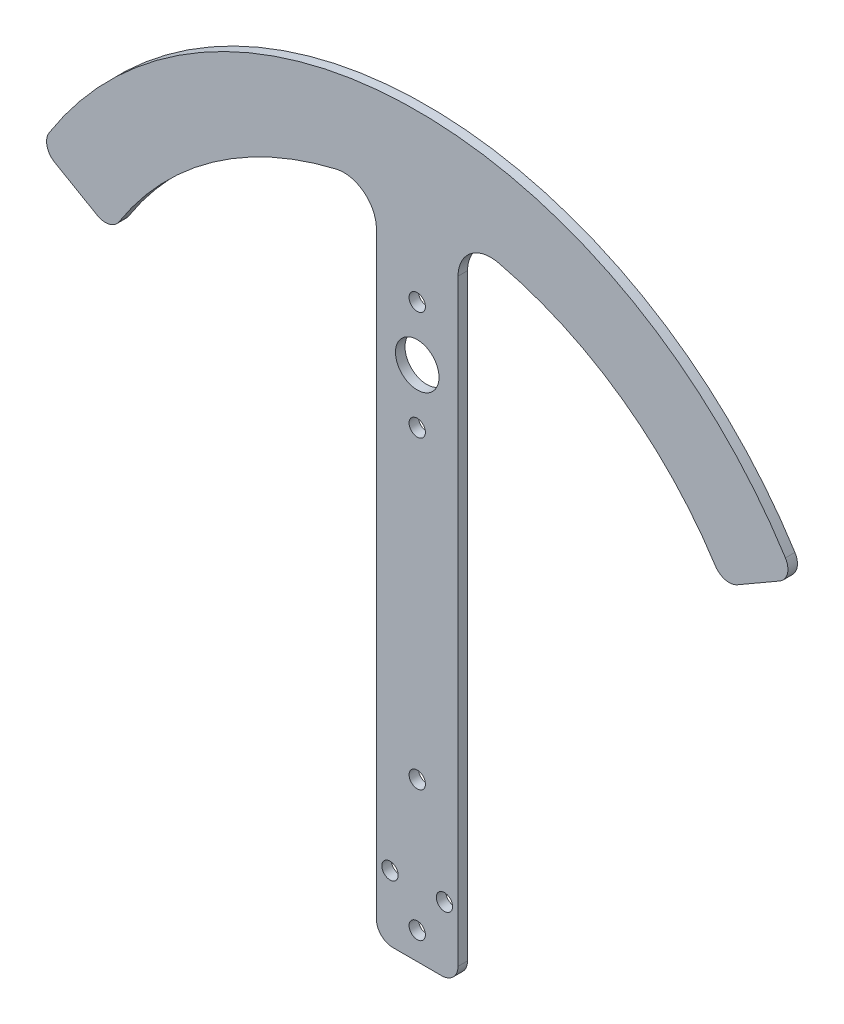
SolidWorks part; units mm, degrees
ref_plane "前视基准面" through (0, 0, 0) normal (0, 0, 1) x (1, 0, 0)
ref_plane "上视基准面" through (0, 0, 0) normal (0, 1, 0) x (1, 0, 0)
ref_plane "右视基准面" through (0, 0, 0) normal (1, 0, 0) x (0, 0, -1)
other "Configuration Table"
sketch "草图1" plane through (0, 0, 0) normal (0, 0, 1) x (1, 0, 0)
  line L0 (0, 0) -> (-69.282, 40) construction
  line L1 (0, 0) -> (69.282, 40) construction
  line L2 (-56.2917, 32.5) -> (-69.282, 40)
  line L3 (56.2917, 32.5) -> (69.282, 40)
  line L4 (0, 0) -> (0, 12.2224) construction
  line L6 (-7.5, 64.5659) -> (7.5, 64.5659)
  line L7 (-7.5, 64.5659) -> (-7.5, -55.4341)
  line L8 (-7.5, -55.4341) -> (7.5, -55.4341)
  line L9 (7.5, 64.5659) -> (7.5, -55.4341)
  arc A0 (69.282, 40) -> (-69.282, 40) centre (0, 0) ccw
  arc A1 (56.2917, 32.5) -> (-56.2917, 32.5) centre (0, 0) ccw
  circle A2 centre (0, -50.4341) radius 1.5
  circle A3 centre (-5, -43.4341) radius 1.5
  circle A4 centre (5, -43.4341) radius 1.5
  circle A5 centre (0, -38.4341) radius 2.5 construction
  circle A7 centre (0, -26.4341) radius 1.5
  circle A8 centre (0, 39.5659) radius 4
  circle A9 centre (0, 29.5659) radius 1.5
  circle A10 centre (0, 49.5659) radius 1.5
  dimension "D1" = 15
  dimension "D7" = 3
  dimension "D10" = 5
  dimension "D13" = 8
  dimension "D2" = 80
  dimension "D3" = 120
  dimension "D4" = 15
  dimension "D5" = 120
  dimension "D6" = 5
  dimension "D8" = 10
  dimension "D9" = 7
  dimension "D11" = 12
  dimension "D12" = 12
  dimension "D14" = 25
  dimension "D15" = 10
  dimension "D16" = 10
extrude "凸台-拉伸1" add sketch "草图1" along normal blind 1.75 contours A1 L3 A0 L2 | L9 L6 L7 L8 A10 A9 A8 A7 A4 A3 A2 | L6 A1
fillet "圆角1" radius 3 6 edges at (7.5, -55.4341, 0.875) (-7.5, -55.4341, 0.875) (69.282, 40, 0.875) (56.2917, 32.5, 0.875) (-69.282, 40, 0.875) (-56.2917, 32.5, 0.875)
fillet "圆角2" radius 6 2 edges at (7.5, 64.5659, 0.875) (-7.5, 64.5659, 0.875)
